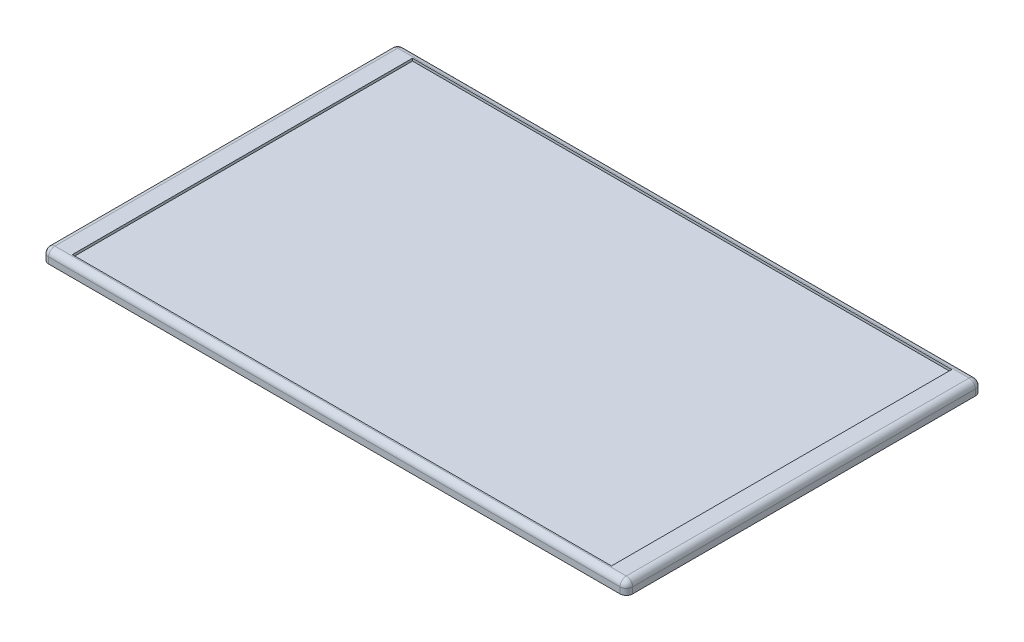
SolidWorks part; units mm, degrees
material "Copper"
ref_plane "Front Plane" through (0, 0, 0) normal (0, 0, 1) x (1, 0, 0)
ref_plane "Top Plane" through (0, 0, 0) normal (0, 1, 0) x (1, 0, 0)
ref_plane "Right Plane" through (0, 0, 0) normal (1, 0, 0) x (0, 0, -1)
sketch "Sketch1" plane through (0, 0, 0) normal (0, 1, 0) x (1, 0, 0)
  line L1 (0, 0) -> (235, 0)
  line L2 (0, 0) -> (0, 143)
  line L3 (0, 143) -> (235, 143)
  line L4 (235, 0) -> (235, 143)
  dimension "D1" = 235
  dimension "D2" = 143
extrude "Boss-Extrude1" add sketch "Sketch1" along normal blind 5
sketch "Sketch2" plane through (0, 5, 0) normal (0, 1, 0) x (1, 0, 0)
  line L0 (117.5, 143) -> (117.5, 0) construction
  line L1 (9.02, 3.0509) -> (225.98, 3.0509)
  line L2 (9.02, 3.0509) -> (9.02, 139.9491)
  line L3 (9.02, 139.9491) -> (225.98, 139.9491)
  line L4 (225.98, 3.0509) -> (225.98, 139.9491)
  line L5 (235, 143) -> (0, 143) construction
  line L6 (0, 0) -> (235, 0) construction
  line L7 (0, 71.5) -> (235, 71.5) construction
  line L8 (0, 143) -> (0, 0) construction
  line L9 (235, 0) -> (235, 143) construction
  point P16 (225.98, 71.5)
  point P17 (117.5, 139.9491)
  dimension "D1" = 256.54
  dimension "D2" = 216.96
extrude "Cut-Extrude1" cut sketch "Sketch2" against normal blind 1
fillet "Fillet1" radius 2.54 8 edges at (235, 2.5, -143) (0, 2.5, -143) (0, 2.5, 0) (235, 2.5, 0) (117.5, 5, 0) (235, 5, -71.5) (117.5, 5, -143) (0, 5, -71.5)
sketch "Sketch3" plane through (0, 4, 0) normal (0, 1, 0) x (1, 0, 0)
  line L0 (205.4959, 307.4323) -> (888.1625, 307.4323) construction
